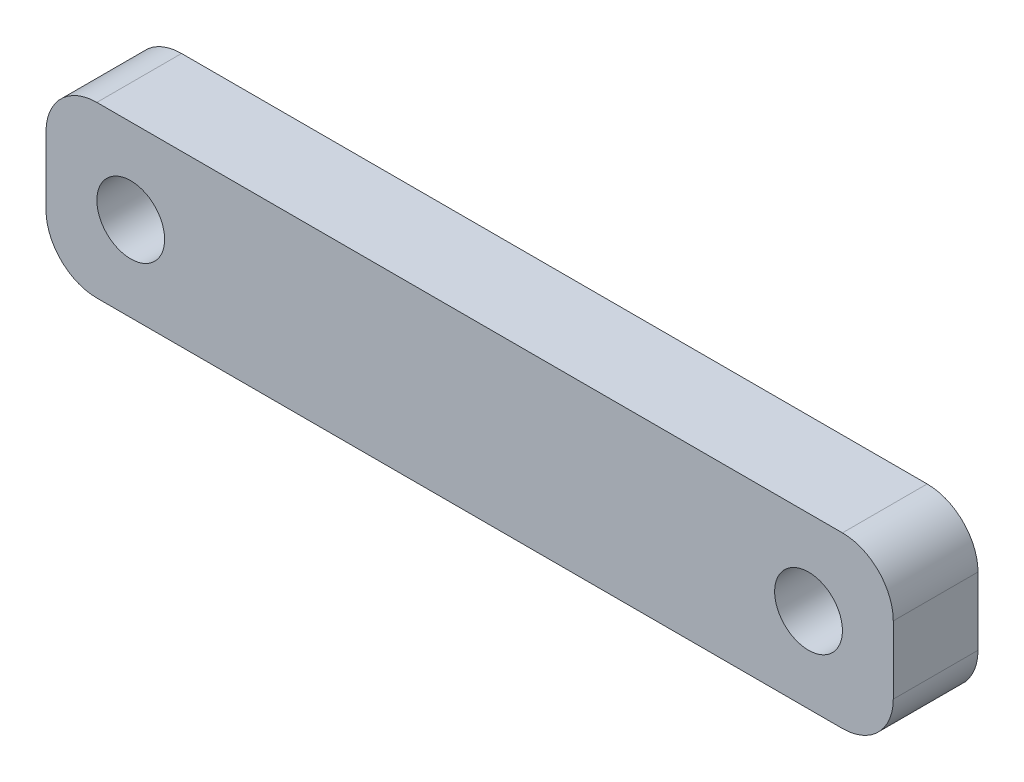
SolidWorks part; units mm, degrees
ref_plane "Plan de face" through (0, 0, 0) normal (0, 0, 1) x (1, 0, 0)
ref_plane "Plan de dessus" through (0, 0, 0) normal (0, 1, 0) x (1, 0, 0)
ref_plane "Plan de droite" through (0, 0, 0) normal (1, 0, 0) x (0, 0, -1)
sketch "Esquisse1" plane through (0, 0, 0) normal (0, 0, 1) x (1, 0, 0)
  line L0 (37.5, -5) -> (12.5, 5) construction
  line L1 (-12.5, 5) -> (37.5, 5)
  line L2 (-12.5, 5) -> (-12.5, -5)
  line L3 (-12.5, -5) -> (37.5, -5)
  line L4 (12.5, 5) -> (12.5, -5)
  line L5 (-12.5, 5) -> (12.5, -5) construction
  line L6 (-12.5, -5) -> (12.5, 5) construction
  line L7 (37.5, 5) -> (12.5, -5) construction
  line L8 (37.5, 5) -> (37.5, -5)
  circle A0 centre (-7.5, 0) radius 2
  circle A1 centre (32.5, 0) radius 2
  point P0 (0, 0)
  point P12 (25, 0)
  dimension "D3" = 4
  dimension "D1" = 25
  dimension "D2" = 10
  dimension "D4" = 5
extrude "Boss.-Extru.1" add sketch "Esquisse1" along normal blind 5 contours L4 L1 L2 L3 A0 | L8 L1 L4 L3 A1
fillet "Congé1" radius 3 1 edges at (37.5, 5, 2.5)
fillet "Congé2" radius 3 1 edges at (37.5, -5, 2.5)
fillet "Congé3" radius 3 1 edges at (-12.5, 5, 2.5)
fillet "Congé4" radius 3 1 edges at (-12.5, -5, 2.5)
